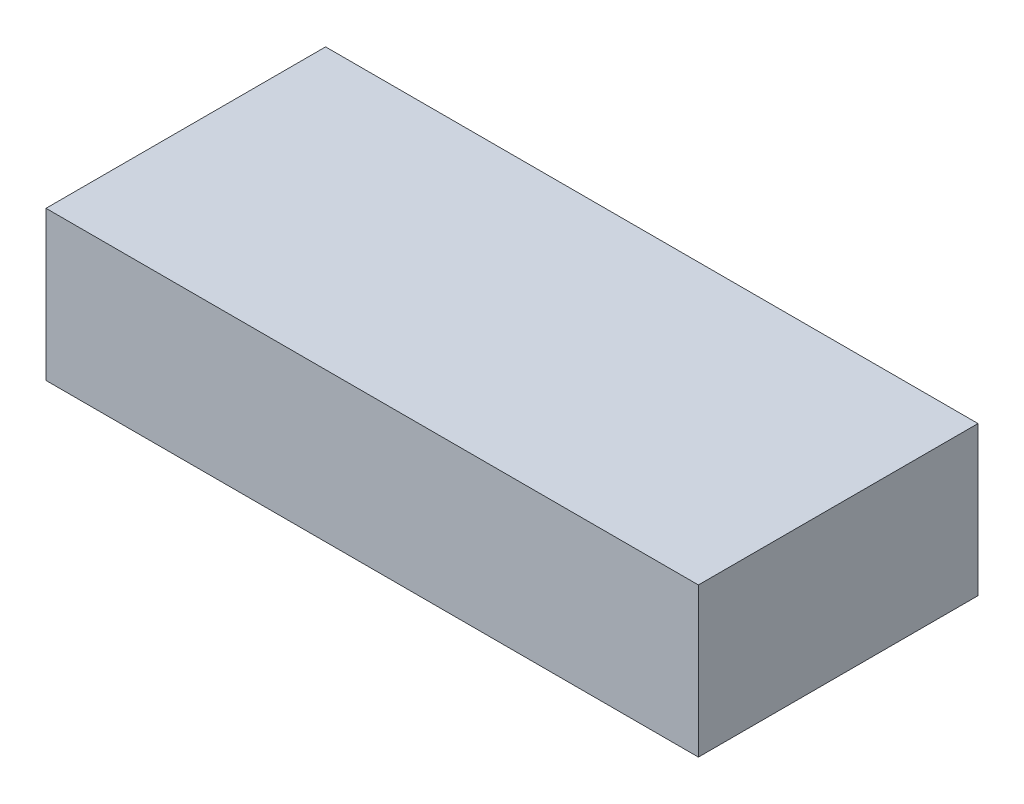
SolidWorks part; units mm, degrees
ref_plane "Front Plane" through (0, 0, 0) normal (0, 0, 1) x (1, 0, 0)
ref_plane "Top Plane" through (0, 0, 0) normal (0, 1, 0) x (1, 0, 0)
ref_plane "Right Plane" through (0, 0, 0) normal (1, 0, 0) x (0, 0, -1)
sketch "Sketch1" plane through (0, 0, 0) normal (0, 1, 0) x (1, 0, 0)
  line L1 (0, 0) -> (7, 0)
  line L2 (0, 0) -> (0, 3)
  line L3 (0, 3) -> (7, 3)
  line L4 (7, 0) -> (7, 3)
  dimension "D1" = 7
  dimension "D2" = 3
extrude "Boss-Extrude1" add sketch "Sketch1" along normal blind 1.6
